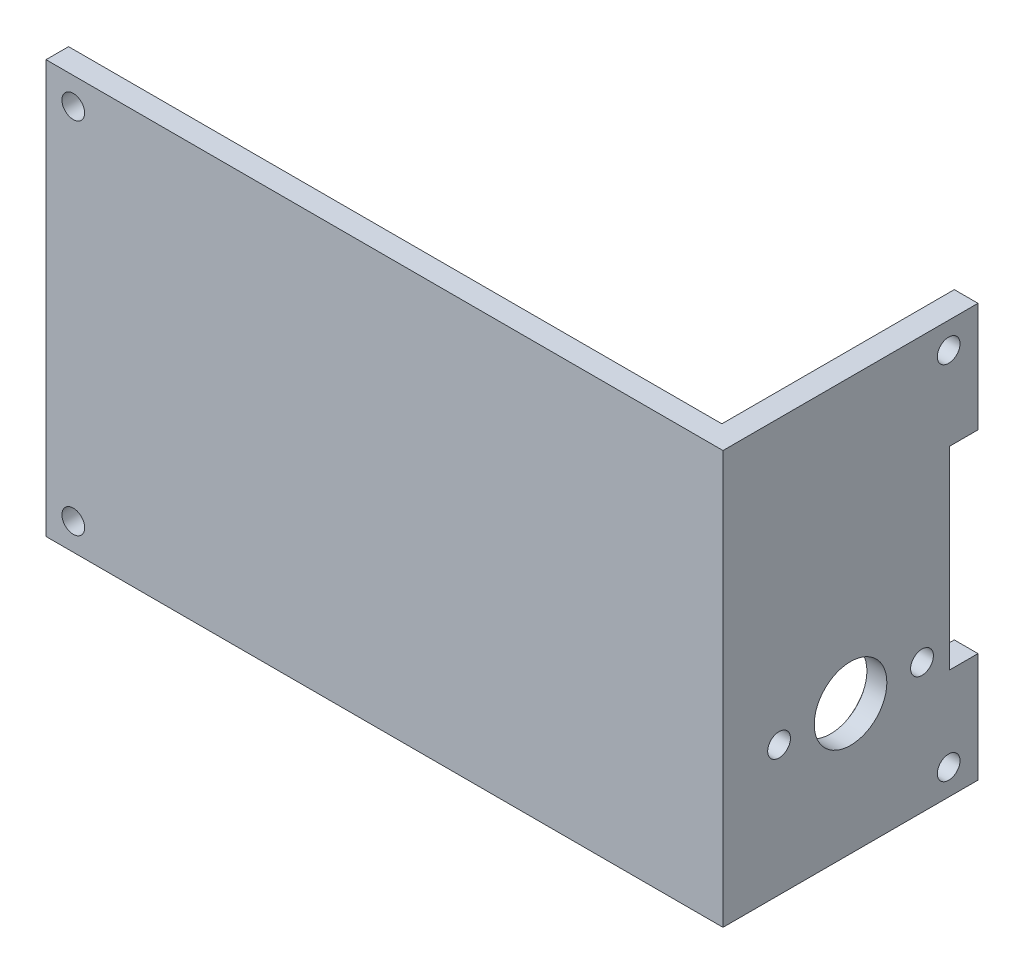
SolidWorks part; units mm, degrees
ref_plane "Front" through (0, 0, 0) normal (0, 0, 1) x (1, 0, 0)
ref_plane "Top" through (0, 0, 0) normal (0, 1, 0) x (1, 0, 0)
ref_plane "Right" through (0, 0, 0) normal (1, 0, 0) x (0, 0, -1)
sketch "Sketch1" plane through (0, 0, 0) normal (0, 1, 0) x (1, 0, 0)
  line L0 (0, 0) -> (86.85, 0)
  line L1 (86.85, 0) -> (86.85, 30.9)
  line L2 (86.85, 30.9) -> (90, 30.9)
  line L3 (90, 30.9) -> (90, -3)
  line L4 (90, -3) -> (0, -3)
  line L5 (0, -3) -> (0, 0)
  dimension "D1" = 3.15
  dimension "D2" = 3
  dimension "D3" = 86.85
  dimension "D4" = 33.9
extrude "Boss-Extrude1" add sketch "Sketch1" along normal blind 54.9
sketch "Sketch2" plane through (90, 0, 0) normal (1, 0, 0) x (0, 0, -1)
  line L0 (27, 54.9) -> (27, 51.45) construction
  line L1 (-3, 54.9) -> (30.9, 54.9) construction
  line L2 (27, 51.45) -> (27, 3.45) construction
  line L3 (27, 3.45) -> (27, 0) construction
  line L4 (-3, 0) -> (30.9, 0) construction
  line L5 (-3, 54.9) -> (-3, 0) construction
  circle A0 centre (27, 51.45) radius 1.51
  circle A1 centre (27, 3.45) radius 1.51
  dimension "D2" = 3.02
  dimension "D1" = 48
  dimension "D3" = 30
extrude "Cut-Extrude1" cut sketch "Sketch2" against normal up to surface (3.15 mm away) up to face at (86.85, 27.45, -15.45)
sketch "Sketch3" plane through (0, 0, 3) normal (0, 0, 1) x (1, 0, 0)
  line L0 (3.625, 54.9) -> (3.625, 51.325) construction
  line L1 (0, 54.9) -> (90, 54.9) construction
  line L2 (3.625, 51.325) -> (3.625, 3.575) construction
  line L3 (3.625, 3.575) -> (3.625, 0) construction
  line L4 (0, 0) -> (90, 0) construction
  line L8 (90, 54.9) -> (90, 0) construction
  circle A0 centre (3.625, 51.325) radius 1.51
  circle A1 centre (3.625, 3.575) radius 1.51
  dimension "D1" = 3.02
  dimension "D2" = 86.375
  dimension "D3" = 47.75
extrude "Cut-Extrude2" cut sketch "Sketch3" against normal up to surface (3 mm away) up to face at (43.425, 27.45, 0)
sketch "Sketch4" plane through (90, 0, 0) normal (1, 0, 0) x (0, 0, -1)
  line L0 (23.4554, 17.3) -> (13.9554, 17.3) construction
  line L1 (13.9554, 17.3) -> (4.4554, 17.3) construction
  circle A0 centre (13.9554, 17.3) radius 4.826
  circle A1 centre (27, 3.45) radius 1.51 construction
  circle A2 centre (23.4554, 17.3) radius 1.515
  circle A3 centre (4.4554, 17.3) radius 1.515
  dimension "D1" = 9.652
  dimension "D2" = 13.85
  dimension "D5" = 3.03
  dimension "D3" = 13.0446
  dimension "D4" = 9.5
extrude "Cut-Extrude3" cut sketch "Sketch4" against normal up to surface (3.15 mm away) up to face at (86.85, 51.45, -28.51)
sketch "Sketch5" plane through (0, 0, 3) normal (0, 0, 1) x (1, 0, 0)
  line L0 (47.6, 54.9) -> (47.6, 47.4)
  line L1 (0, 54.9) -> (90, 54.9) construction
  line L2 (47.6, 47.4) -> (43.4, 47.4)
  line L3 (43.4, 47.4) -> (30.7, 54.9)
  line L4 (47.6, 54.9) -> (30.7, 54.9)
  line L5 (90, 27.45) -> (0, 27.45) construction
  line L6 (90, 54.9) -> (90, 0) construction
  line L7 (0, 54.9) -> (0, 0) construction
  line L8 (47.6, 0) -> (30.7, 0)
  line L9 (43.4, 7.5) -> (30.7, 0)
  line L10 (47.6, 7.5) -> (43.4, 7.5)
  line L11 (47.6, 0) -> (47.6, 7.5)
  dimension "D1" = 7.5
  dimension "D2" = 4.2
  dimension "D3" = 16.9
  dimension "D4" = 42.4
extrude "Cut-Extrude4" [suppressed] cut sketch "Sketch5" against normal up to surface (3 mm away)
sketch "Sketch6" plane through (86.85, 0, 0) normal (-1, 0, 0) x (0, 0, 1)
  circle A0 centre (-13.9554, 17.3) radius 5.5
  dimension "D1" = 11
extrude "Cut-Extrude5" cut sketch "Sketch6" against normal blind 0.5
sketch "Sketch7" plane through (0, 0, 0) normal (0, 0, -1) x (-1, 0, 0)
  line L1 (11.6094, -14.7253) -> (-64.0664, -14.7253)
  line L2 (11.6094, -14.7253) -> (11.6094, 78.1399)
  line L3 (11.6094, 78.1399) -> (-64.0664, 78.1399)
  line L4 (-64.0664, -14.7253) -> (-64.0664, 78.1399)
extrude "Cut-Extrude6" [suppressed] cut sketch "Sketch7" against normal blind 10
sketch "Sketch8" plane through (90, 0, 0) normal (1, 0, 0) x (0, 0, -1)
  line L0 (30.9, 54.9) -> (30.9, 0) construction
  line L1 (30.9, 14.5723) -> (27.1011, 14.5723)
  line L2 (30.9, 14.5723) -> (30.9, 40.3277)
  line L3 (30.9, 40.3277) -> (27.1011, 40.3277)
  line L4 (27.1011, 14.5723) -> (27.1011, 40.3277)
  line L5 (30.9, 0) -> (30.9, 14.5723) construction
  line L6 (30.9, 40.3277) -> (30.9, 54.9) construction
  dimension "D1" = 25.7555
extrude "Cut-Extrude7" cut sketch "Sketch8" against normal up to surface (3.15 mm away) up to face at (86.85, 17.3, -8.4554)
